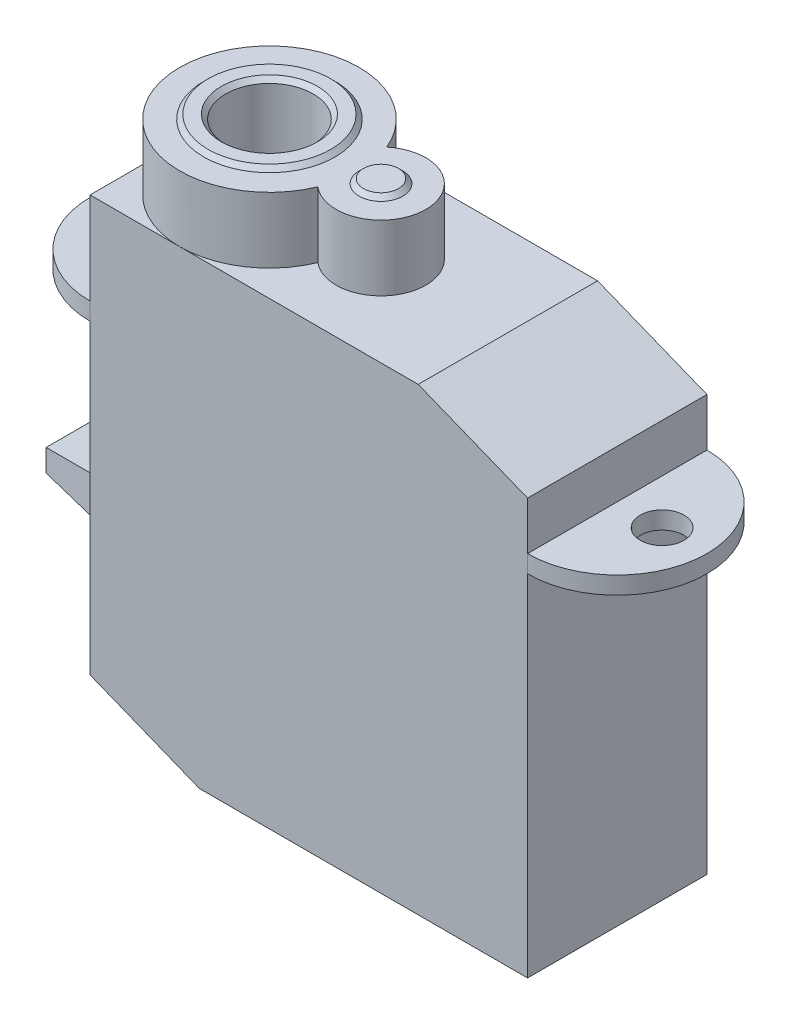
SolidWorks part; units mm, degrees
material "Custom Plastic"
ref_plane "Front Plane" through (0, 0, 0) normal (0, 0, 1) x (1, 0, 0)
ref_plane "Top Plane" through (0, 0, 0) normal (0, 1, 0) x (1, 0, 0)
ref_plane "Right Plane" through (0, 0, 0) normal (1, 0, 0) x (0, 0, -1)
sketch "Sketch1" plane through (0, 0, 0) normal (0, 1, 0) x (1, 0, 0)
  line L1 (0, 0) -> (20, 0)
  line L2 (0, 0) -> (0, -8.2)
  line L3 (0, -8.2) -> (20, -8.2)
  line L4 (20, 0) -> (20, -8.2)
  dimension "D1" = 20
  dimension "D2" = 8.2
extrude "Boss-Extrude1" add sketch "Sketch1" along normal blind 21
sketch "Sketch2" plane through (20, 0, 0) normal (1, 0, 0) x (0, 0, -1)
  line L0 (-8.2, 21) -> (-8.2, 0) construction
  line L1 (-8.2, 16.8) -> (0, 16.8)
  line L2 (-8.2, 16.8) -> (-8.2, 16)
  line L3 (-8.2, 16) -> (0, 16)
  line L4 (0, 16.8) -> (0, 16)
  line L5 (0, 21) -> (0, 0) construction
  line L6 (-8.2, 0) -> (0, 0) construction
  dimension "D1" = 16
  dimension "D2" = 0.8
extrude "Boss-Extrude2" add sketch "Sketch2" along normal blind 5 contours L3 L4 L1 L2
sketch "Sketch3" plane through (0, 0, 0) normal (-1, 0, 0) x (0, 0, 1)
  line L0 (0, 21) -> (0, 0) construction
  line L1 (0, 16) -> (8.2, 16)
  line L2 (0, 16) -> (0, 16.8)
  line L3 (0, 16.8) -> (8.2, 16.8)
  line L4 (8.2, 16) -> (8.2, 16.8)
  line L5 (8.2, 21) -> (8.2, 0) construction
  line L6 (0, 0) -> (8.2, 0) construction
  dimension "D1" = 16
  dimension "D2" = 0.8
extrude "Boss-Extrude3" add sketch "Sketch3" along normal blind 5
sketch "Sketch4" plane through (0, 0, 8.2) normal (0, 0, 1) x (1, 0, 0)
  line L0 (20, 19) -> (15, 21)
  line L1 (20, 21) -> (20, 16.8) construction
  line L2 (0, 21) -> (20, 21) construction
  line L3 (15, 21) -> (20, 21)
  line L4 (20, 21) -> (20, 19)
  dimension "D1" = 5
  dimension "D2" = 2
extrude "Cut-Extrude1" cut sketch "Sketch4" against normal up to next
ref_plane "Plane1" through (0, 16.8, 0) normal (0, 1, 0) x (1, 0, 0)
sketch "Sketch8" plane through (0, 16.8, 0) normal (0, 1, 0) x (1, 0, 0)
  line L0 (0, -8.2) -> (0, 0) construction
  line L1 (20, -8.2) -> (20, 0) construction
  line L4 (-5, 0) -> (0, 0)
  line L6 (-5, -8.2) -> (0, -8.2) construction
  line L7 (-5, -8.2) -> (0, -8.2)
  line L9 (20, -8.2) -> (25, -8.2)
  line L10 (25, -8.2) -> (20, -8.2) construction
  line L13 (25, 0) -> (20, 0) construction
  line L14 (25, 0) -> (20, 0)
  line L15 (25, 0) -> (25, -8.2)
  line L16 (-5, 0) -> (-5, -8.2)
  arc A0 (0, 0) -> (0, -8.2) centre (0, -4.1) ccw
  arc A1 (20, -8.2) -> (20, 0) centre (20, -4.1) ccw
extrude "Cut-Extrude2" cut sketch "Sketch8" against normal up to next
sketch "Sketch9" plane through (0, 16.8, 0) normal (0, 1, 0) x (1, 0, 0)
  line L0 (-4.1, -4.1) -> (0, -4.1) construction
  line L1 (20, -4.1) -> (24.1, -4.1) construction
  line L2 (20, -8.2) -> (20, 0) construction
  arc A0 (0, 0) -> (0, -8.2) centre (0, -4.1) ccw construction
  arc A1 (20, -8.2) -> (20, 0) centre (20, -4.1) ccw construction
  circle A4 centre (-2.05, -4.1) radius 1
  circle A5 centre (22.05, -4.1) radius 1
  dimension "D1" = 2
  dimension "D2" = 2
hole_wizard "Ø2.0 (2) Diameter Hole1" positions "3DSketch1" profile "Sketch14" hole size "Ø2.0" standard "ANSI Metric" end condition up to next
sketch3d "3DSketch1"
  point P0 (-2.05, 16.8, 4.1)
  point P3 (22.05, 16.8, 4.1)
sketch "Sketch14" plane through (-2.05, 16.8, 4.1) normal (1, 0, 0) x (0, 0, 1)
  line L0 (0, 0) -> (0, 0.8)
  line L1 (0, 0.8) -> (1, 0.8)
  line L2 (1, 0.8) -> (1, 0)
  line L5 (1, 0) -> (0, 0)
  line L11 (0, -6.35) -> (0, 107.95) construction
  dimension "Thru Hole Dia." = 2
  dimension "Thru Hole Depth" = 0.8
sketch "Sketch10" plane through (0, 21, 0) normal (0, 1, 0) x (1, 0, 0)
  line L0 (15, 0) -> (0, 0) construction
  line L1 (0, -8.2) -> (15, -8.2) construction
  line L2 (0, 0) -> (0, -8.2) construction
  line L3 (9.2, 0) -> (9.2, -4.1) construction
  line L4 (9.2, -4.1) -> (8.2, -4.1) construction
  arc A0 (7.886, -2.5265) -> (7.886, -5.6735) centre (4.1, -4.1) ccw
  arc A1 (7.886, -5.6735) -> (7.886, -2.5265) centre (9.2, -4.1) ccw
  arc A2 (7.886, -2.5265) -> (7.886, -5.6735) centre (4.1, -4.1) cw construction
  point P11 (9.2, -2.05)
  dimension "D1" = 1
extrude "Boss-Extrude6" add sketch "Sketch10" along normal blind 3
sketch "Sketch11" plane through (0, 0, 8.2) normal (0, 0, 1) x (1, 0, 0)
  line L0 (0, 0) -> (0, 2)
  line L1 (0, 16) -> (0, 0) construction
  line L2 (0, 2) -> (5, 0)
  line L3 (0, 0) -> (20, 0) construction
  line L4 (5, 0) -> (0, 0)
  dimension "D1" = 2
  dimension "D2" = 5
extrude "Cut-Extrude4" cut sketch "Sketch11" against normal up to next
sketch "Sketch12" plane through (0, 0, 0) normal (-1, 0, 0) x (0, 0, 1)
  line L0 (4.1, 16) -> (4.1, 0) construction
  line L1 (0, 16) -> (8.2, 16) construction
  line L2 (0, 0) -> (8.2, 0) construction
  line L4 (1, 7) -> (7.2, 7)
  line L5 (1, 7) -> (1, 9)
  line L6 (1, 9) -> (7.2, 9)
  line L7 (7.2, 7) -> (7.2, 9)
  line L8 (1, 7) -> (7.2, 9) construction
  line L9 (1, 9) -> (7.2, 7) construction
  line L10 (0, 16) -> (0, 2) construction
  point P8 (4.1, 8)
  dimension "D1" = 2
  dimension "D2" = 1
extrude "Boss-Extrude7" add sketch "Sketch12" along normal blind 3.5 draft 8
sketch "Sketch15" plane through (0, 24, 0) normal (0, 1, 0) x (1, 0, 0)
  circle A0 centre (4.1, -4.1) radius 2
  dimension "D1" = 4
extrude "Cut-Extrude5" cut sketch "Sketch15" against normal blind 5
sketch "Sketch17" plane through (0, 24, 0) normal (0, 1, 0) x (1, 0, 0)
  circle A0 centre (4.1, -4.1) radius 2
  circle A1 centre (4.1, -4.1) radius 3
  circle A2 centre (9.2, -4.1) radius 1
  dimension "D1" = 4
  dimension "D2" = 1
  dimension "D3" = 2
extrude "Boss-Extrude10" add sketch "Sketch17" along normal blind 0.2 draft 45
